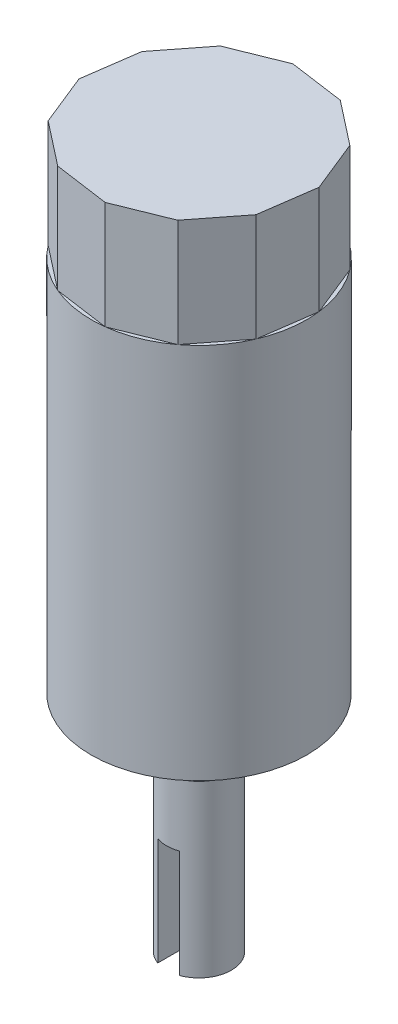
SolidWorks part; units mm, degrees
ref_plane "前视基准面" through (0, 0, 0) normal (0, 0, 1) x (1, 0, 0)
ref_plane "上视基准面" through (0, 0, 0) normal (0, 1, 0) x (1, 0, 0)
ref_plane "右视基准面" through (0, 0, 0) normal (1, 0, 0) x (0, 0, -1)
other "Configuration Table"
sketch "草图1" plane through (0, 0, 0) normal (0, 1, 0) x (1, 0, 0)
  circle A0 centre (0, 0) radius 1.5
  dimension "D1" = 3
extrude "凸台-拉伸1" add sketch "草图1" along normal blind 7.9
sketch "草图2" plane through (0, 0, 0) normal (0, -1, 0) x (1, 0, 0)
  line L0 (0, 0) -> (0, 50000) construction
  line L1 (-0.5, 1.4142) -> (-0.5, -1.4142)
  line L2 (0.5, -1.4142) -> (0.5, 1.4142)
  circle A0 centre (0, 0) radius 1.5 construction
  arc A1 (-0.5, 1.4142) -> (0.5, 1.4142) centre (0, 0) cw
  arc A2 (-0.5, -1.4142) -> (0.5, -1.4142) centre (0, 0) ccw
  dimension "D1" = 1
extrude "切除-拉伸1" cut sketch "草图2" against normal blind 5
sketch "草图3" plane through (0, 7.9, 0) normal (0, 1, 0) x (1, 0, 0)
  circle A0 centre (0, 0) radius 1
  dimension "D1" = 2
extrude "凸台-拉伸2" add sketch "草图3" along normal blind 2.5
sketch "草图4" plane through (0, 10.4, 0) normal (0, 1, 0) x (1, 0, 0)
  circle A0 centre (0, 0) radius 5
  dimension "D1" = 10
extrude "凸台-拉伸3" add sketch "草图4" along normal blind 22.5
sketch "草图5" plane through (0, 32.9, 0) normal (0, 1, 0) x (1, 0, 0)
  line L1 (1.955, 4.602) -> (-0.6079, 4.9629)
  line L2 (-0.6079, 4.9629) -> (-3.0079, 3.994)
  line L3 (-3.0079, 3.994) -> (-4.602, 1.955)
  line L4 (-4.602, 1.955) -> (-4.9629, -0.6079)
  line L5 (-4.9629, -0.6079) -> (-3.994, -3.0079)
  line L6 (-3.994, -3.0079) -> (-1.955, -4.602)
  line L7 (-1.955, -4.602) -> (0.6079, -4.9629)
  line L8 (0.6079, -4.9629) -> (3.0079, -3.994)
  line L9 (3.0079, -3.994) -> (4.602, -1.955)
  line L10 (4.602, -1.955) -> (4.9629, 0.6079)
  line L11 (4.9629, 0.6079) -> (3.994, 3.0079)
  line L12 (3.994, 3.0079) -> (1.955, 4.602)
  circle A0 centre (0, 0) radius 4.8296 construction
  circle M13 centre (0, 0) radius 5
extrude "切除-拉伸3" cut sketch "草图5" against normal blind 5 contours L7 M13 | L8 M13 | L9 M13 | L10 M13 | L11 M13 | L6 M13 | L5 M13 | L4 M13 | L3 M13 | L2 M13 | L1 M13 | L12 M13
